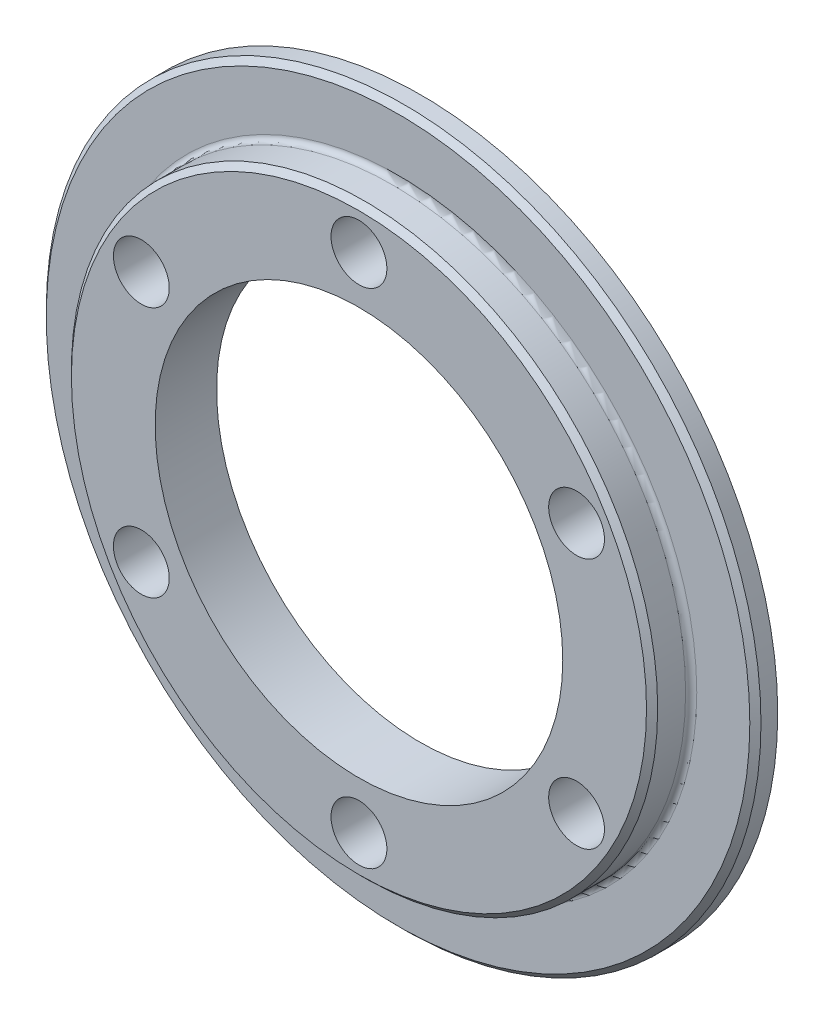
SolidWorks part; units mm, degrees
ref_plane "Ön Düzlem" through (0, 0, 0) normal (0, 0, 1) x (1, 0, 0)
ref_plane "Üst Düzlem" through (0, 0, 0) normal (0, 1, 0) x (1, 0, 0)
ref_plane "Sağ Düzlem" through (0, 0, 0) normal (1, 0, 0) x (0, 0, -1)
sketch "Çizim1" plane through (0, 0, 0) normal (0, 0, 1) x (1, 0, 0)
  circle A0 centre (0, 0) radius 64
  circle A1 centre (0, 0) radius 36.5
  dimension "D1" = 128
  dimension "D2" = 73
extrude "Yükseklik-Ekstrüzyon1" add sketch "Çizim1" along normal blind 11
sketch "Çizim2" plane through (0, 0, 11) normal (0, 0, 1) x (1, 0, 0)
  circle A0 centre (0, 0) radius 52.5
  circle A1 centre (0, 0) radius 79.9584
  dimension "D1" = 105
extrude "Kes-Ekstrüzyon1" cut sketch "Çizim2" against normal blind 7
fillet "Radyus1" radius 1 1 edges at (52.5, 0, 4)
chamfer "Pah1" distance 1 angle 45 2 edges at (52.5, 0, 11) (64, 0, 4)
sketch "Çizim3" plane through (0, 0, 0) normal (0, 0, -1) x (-1, 0, 0)
  circle A1 centre (0, 45) radius 5
  circle A3 centre (38.9711, 22.5) radius 5
  circle A4 centre (38.9711, -22.5) radius 5
  circle A5 centre (0, -45) radius 5
  circle A6 centre (-38.9711, -22.5) radius 5
  circle A7 centre (-38.9711, 22.5) radius 5
  point P23 (0, 0)
  dimension "D2" = 10
  dimension "D3" = 6
extrude "Kes-Ekstrüzyon2" cut sketch "Çizim3" against normal blind 60
